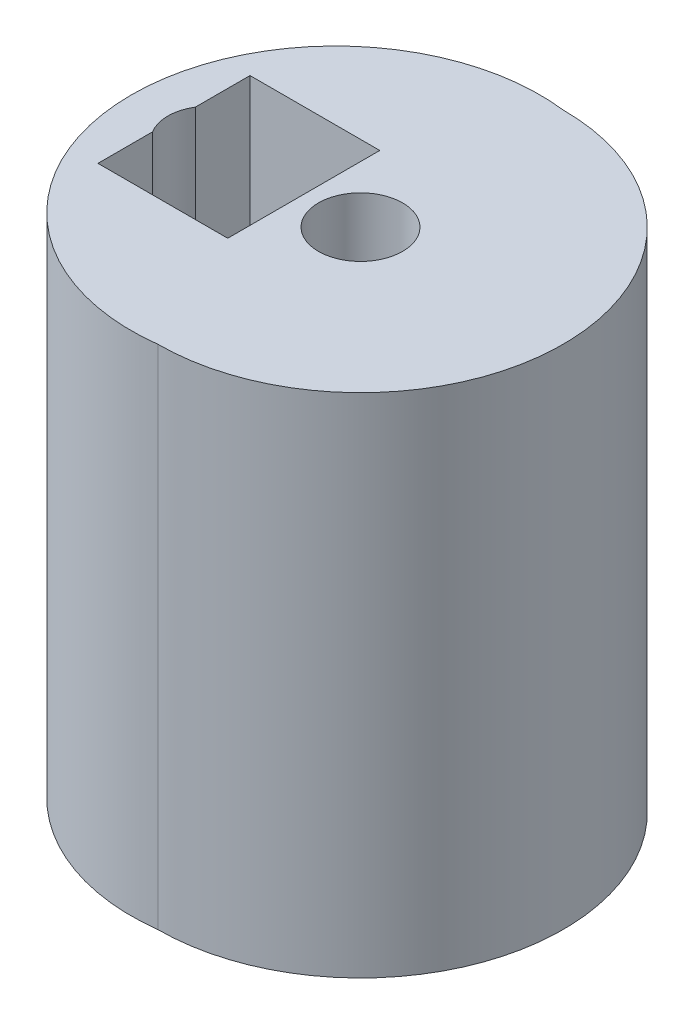
SolidWorks part; units mm, degrees
ref_plane "Спереди" through (0, 0, 0) normal (0, 0, 1) x (1, 0, 0)
ref_plane "Сверху" through (0, 0, 0) normal (0, 1, 0) x (1, 0, 0)
ref_plane "Справа" through (0, 0, 0) normal (1, 0, 0) x (0, 0, -1)
sketch "Sketch1" plane through (0, 0, 0) normal (0, 1, 0) x (1, 0, 0)
  circle A0 centre (0, 0) radius 20 construction
  arc A1 (0, 20) -> (0, -20) centre (0, 0) cw
  arc A2 (0, 20) -> (0, -20) centre (-2.4541, 0) ccw
  dimension "D1" = 40
  dimension "D2" = 20.15
extrude "Boss-Extrude1" add sketch "Sketch1" along normal blind 50
sketch "Sketch2" plane through (0, 0, 0) normal (0, -1, 0) x (1, 0, 0)
  circle A0 centre (0, 0) radius 13.5
  point P3 (0, 0)
  point P4 (0, 0)
  dimension "D1" = 27
extrude "Cut-Extrude1" cut sketch "Sketch2" against normal offset from surface (32 mm away) 18 up to face at (-1.302, 50, 0)
sketch "Sketch3" plane through (0, 50, 0) normal (0, 1, 0) x (1, 0, 0)
  circle A0 centre (0, 0) radius 4.15
  dimension "D1" = 8.3
extrude "Cut-Extrude2" cut sketch "Sketch3" against normal through all
sketch "Sketch4" plane through (0, 50, 0) normal (0, 1, 0) x (1, 0, 0)
  line L0 (0, 0) -> (-22.6041, 0) construction
  line L1 (-18.4, 7.5) -> (-18.4, 2.1071)
  line L2 (-5.6, -7.5) -> (-18.4, -7.5)
  line L3 (-5.6, -7.5) -> (-5.6, 7.5)
  line L4 (-5.6, 7.5) -> (-18.4, 7.5)
  line L5 (-18.4, -7.5) -> (-18.4, 7.5) construction
  line L6 (-5.6, -7.5) -> (-18.4, 7.5) construction
  line L7 (-5.6, 7.5) -> (-18.4, -7.5) construction
  line L8 (-18.4, -2.1071) -> (-18.4, -7.5)
  circle A1 centre (-15, 0) radius 4 construction
  arc A2 (-18.4, 2.1071) -> (-18.4, -2.1071) centre (-15, 0) ccw
  arc A3 (0, 20) -> (0, -20) centre (-2.4541, 0) ccw construction
  point P3 (0, 0)
  point P9 (-12, 0)
  point P16 (0, 0)
  point P19 (-22.6041, 0)
  dimension "D2" = 8
  dimension "D1" = 15
  dimension "D3" = 15
  dimension "D4" = 12.8
  dimension "D5" = 12
extrude "Cut-Extrude3" cut sketch "Sketch4" against normal through all
